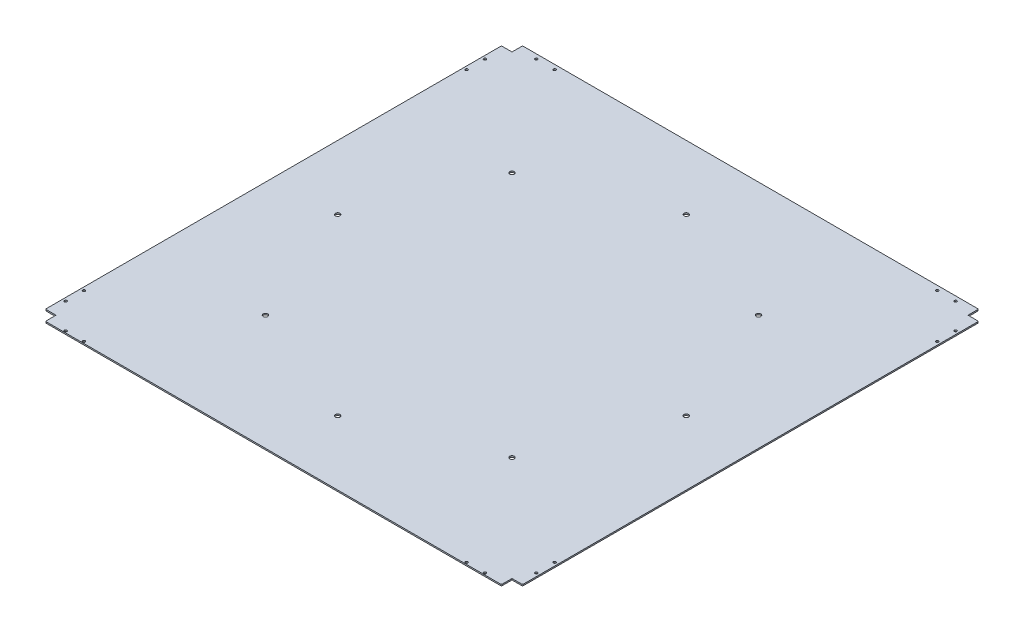
SolidWorks part; units mm, degrees
ref_plane "前视基准面" through (0, 0, 0) normal (0, 0, 1) x (1, 0, 0)
ref_plane "上视基准面" through (0, 0, 0) normal (0, 1, 0) x (1, 0, 0)
ref_plane "右视基准面" through (0, 0, 0) normal (1, 0, 0) x (0, 0, -1)
sketch "草图1" plane through (0, 0, 0) normal (0, 1, 0) x (1, 0, 0)
  line L0 (0, 458.1262) -> (0, -217.1437) construction
  line L5 (-65.3734, 0) -> (70.3309, 0) construction
  line L6 (0, 520) -> (-495, 520)
  line L7 (-497, 518) -> (-497, 497)
  line L10 (-497, 497) -> (-518, 497)
  line L11 (-520, 495) -> (-520, 0)
  line L12 (520, 0) -> (520, 495)
  line L13 (518, 497) -> (497, 497)
  line L14 (497, 497) -> (497, 518)
  line L15 (495, 520) -> (0, 520)
  line L16 (0, -520) -> (495, -520)
  line L17 (497, -518) -> (497, -497)
  line L18 (497, -497) -> (518, -497)
  line L19 (520, -495) -> (520, 0)
  line L20 (-520, 0) -> (-520, -495)
  line L21 (-518, -497) -> (-497, -497)
  line L22 (-497, -497) -> (-497, -518)
  line L23 (-495, -520) -> (0, -520)
  arc A0 (-497, 518) -> (-495, 520) centre (-495, 518) cw
  arc A1 (-520, 495) -> (-518, 497) centre (-518, 495) cw
  arc A2 (518, 497) -> (520, 495) centre (518, 495) cw
  arc A3 (495, 520) -> (497, 518) centre (495, 518) cw
  arc A4 (497, -518) -> (495, -520) centre (495, -518) cw
  arc A5 (520, -495) -> (518, -497) centre (518, -495) cw
  arc A6 (-518, -497) -> (-520, -495) centre (-518, -495) cw
  arc A7 (-495, -520) -> (-497, -518) centre (-495, -518) cw
  point P13 (-497, 520)
  point P17 (-520, 497)
  point P46 (0, 0)
  dimension "D5" = 2
  dimension "D6" = 2
  dimension "D1" = 520
  dimension "D2" = 520
  dimension "D3" = 23
  dimension "D4" = 23
  dimension "D7" = 4
extrude "凸台-拉伸3" add sketch "草图1" along normal blind 3 contours L6 A0 L7 L10 A1 L11 L20 A6 L21 L22 A7 L23 L16 A4 L17 L18 A5 L19 L12 A2 L13 L14 A3 L15
sketch "草图2" plane through (0, 3, 0) normal (0, 1, 0) x (1, 0, 0)
  line L0 (214.8682, 0) -> (0, 0) construction
  line L1 (0, -133.6025) -> (0, 123.7667) construction
  line L2 (-316.34, 0) -> (-1482.0742, 0) construction
  line L15 (506.5258, 510) -> (465.2228, 510) construction
  line L17 (497, 497) -> (497, 518) construction
  line L18 (495, 520) -> (-495, 520) construction
  circle A1 centre (380, 0) radius 5
  circle A10 centre (268.7006, -268.7006) radius 5
  circle A11 centre (0, -380) radius 5
  circle A12 centre (-268.7006, -268.7006) radius 5
  circle A13 centre (-380, 0) radius 5
  circle A14 centre (-268.7006, 268.7006) radius 5
  circle A15 centre (0, 380) radius 5
  circle A16 centre (268.7006, 268.7006) radius 5
  circle A17 centre (457, 510) radius 2.75
  circle A18 centre (417, 510) radius 2.75
  circle A19 centre (-417, 510) radius 2.75
  circle A20 centre (-457, 510) radius 2.75
  circle A21 centre (513, -460) radius 2.75
  circle A22 centre (513, -420) radius 2.75
  circle A23 centre (513, 454) radius 2.75
  circle A24 centre (513, 414) radius 2.75
  circle A25 centre (-457, -516) radius 2.75
  circle A26 centre (-417, -516) radius 2.75
  circle A27 centre (457, -516) radius 2.75
  circle A28 centre (417, -516) radius 2.75
  circle A29 centre (-513, 454) radius 2.75
  circle A30 centre (-513, 414) radius 2.75
  circle A31 centre (-513, -460) radius 2.75
  circle A32 centre (-513, -420) radius 2.75
  point P26 (0, 0)
  point P38 (0, 0)
  point P65 (0, -3)
  dimension "D1" = 8
  dimension "D4" = 5.5
  dimension "D2" = 380
  dimension "D3" = 10
  dimension "D5" = 40
  dimension "D6" = 2
  dimension "D7" = 4
extrude "切除-拉伸1" cut sketch "草图2" against normal through all
